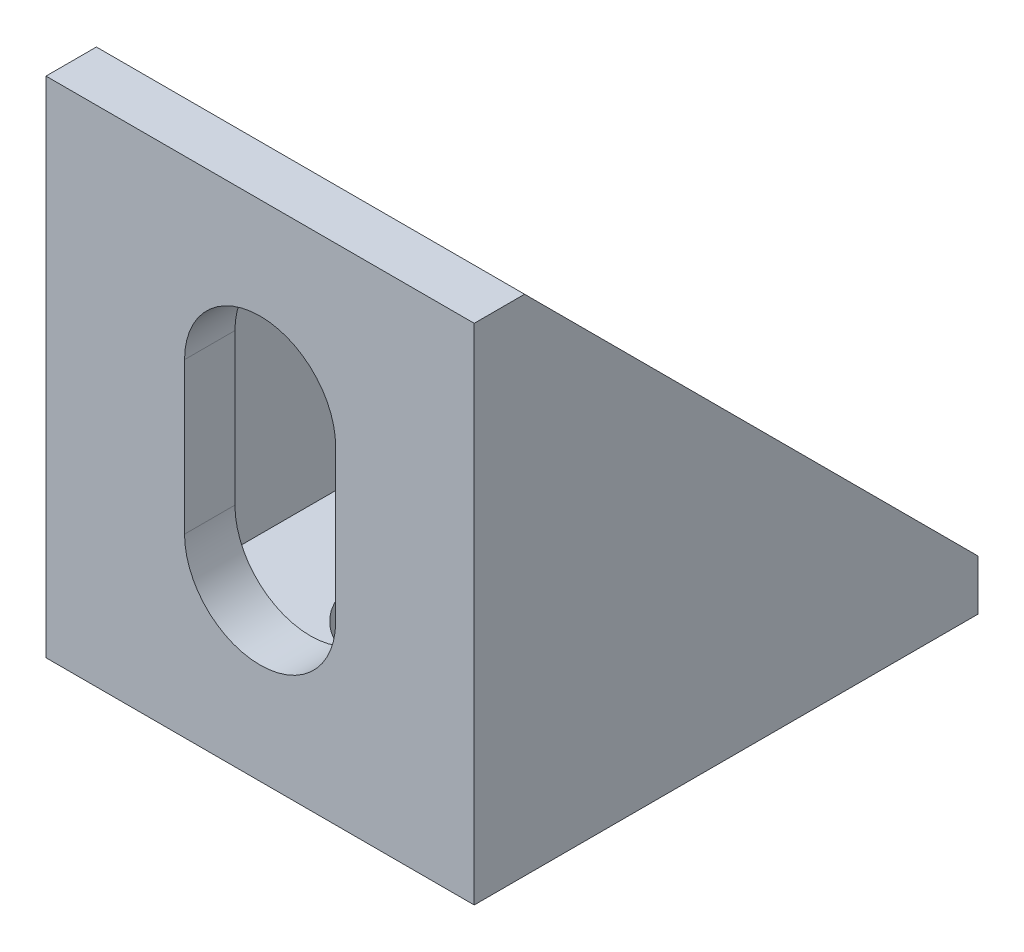
SolidWorks part; units mm, degrees
material "1060 Alloy"
ref_plane "Front Plane" through (0, 0, 0) normal (0, 0, 1) x (1, 0, 0)
ref_plane "Top Plane" through (0, 0, 0) normal (0, 1, 0) x (1, 0, 0)
ref_plane "Right Plane" through (0, 0, 0) normal (1, 0, 0) x (0, 0, -1)
sketch "Sketch1" plane through (0, 0, 0) normal (1, 0, 0) x (0, 0, -1)
  line L0 (0, 0) -> (0, 20)
  line L1 (0, 20) -> (2, 20)
  line L2 (2, 20) -> (20, 2)
  line L3 (20, 2) -> (20, 0)
  line L4 (20, 0) -> (0, 0)
  dimension "D1" = 20
  dimension "D2" = 20
  dimension "D3" = 2
  dimension "D4" = 2
extrude "Boss-Extrude1" add sketch "Sketch1" along normal blind 17
sketch "Sketch2" plane through (0, 20, 0) normal (0, 1, 0) x (1, 0, 0)
  line L0 (17, 2) -> (0, 2) construction
  line L1 (15, 2) -> (2, 2)
  line L2 (15, 2) -> (15, 20)
  line L3 (15, 20) -> (2, 20)
  line L4 (2, 2) -> (2, 20)
  line L5 (17, 20) -> (17, 2) construction
  dimension "D1" = 13
  dimension "D2" = 2
  dimension "D3" = 18
extrude "Cut-Extrude1" cut sketch "Sketch2" against normal blind 18
sketch "Sketch3" plane through (0, 0, -2) normal (0, 0, -1) x (-1, 0, 0)
  line L0 (-8.5, 7) -> (-8.5, 13) construction
  line L1 (-11.5, 7) -> (-11.5, 13)
  line L2 (-5.5, 7) -> (-5.5, 13)
  line L3 (-17, 20) -> (-17, 0) construction
  arc A0 (-11.5, 7) -> (-5.5, 7) centre (-8.5, 7) ccw
  arc A1 (-5.5, 13) -> (-11.5, 13) centre (-8.5, 13) ccw
  point P2 (-8.5, 10)
  dimension "D1" = 3
  dimension "D2" = 6
  dimension "D3" = 8.5
  dimension "D4" = 10
extrude "Cut-Extrude2" cut sketch "Sketch3" against normal up to next
sketch "Sketch4" plane through (0, 2, 0) normal (0, 1, 0) x (1, 0, 0)
  line L0 (8.5, 13) -> (8.5, 7) construction
  line L1 (11.5, 13) -> (11.5, 7)
  line L2 (5.5, 13) -> (5.5, 7)
  arc A0 (11.5, 13) -> (5.5, 13) centre (8.5, 13) ccw
  arc A1 (5.5, 7) -> (11.5, 7) centre (8.5, 7) ccw
  point P2 (8.5, 10)
  dimension "D1" = 3
  dimension "D2" = 6
  dimension "D3" = 10
  dimension "D4" = 8.5
extrude "Cut-Extrude3" cut sketch "Sketch4" against normal up to next
